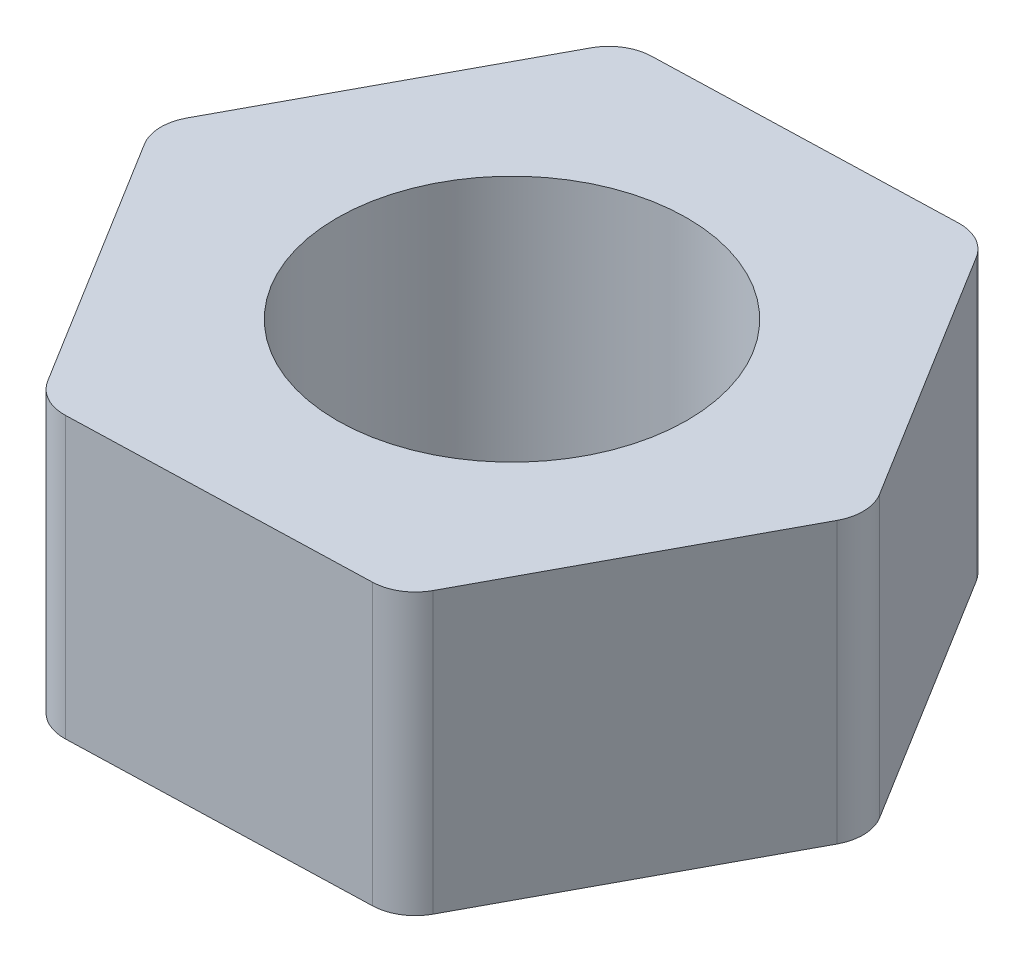
SolidWorks part; units mm, degrees
ref_plane "前视基准面" through (0, 0, 0) normal (0, 0, 1) x (1, 0, 0)
ref_plane "上视基准面" through (0, 0, 0) normal (0, 1, 0) x (1, 0, 0)
ref_plane "右视基准面" through (0, 0, 0) normal (1, 0, 0) x (0, 0, -1)
sketch "Sketch1" plane through (0, 0, 0) normal (0, 1, 0) x (1, 0, 0)
  line L1 (2.0955, -3.3881) -> (3.9819, 0.1207)
  line L2 (3.9819, 0.1207) -> (1.8864, 3.5088)
  line L3 (1.8864, 3.5088) -> (-2.0955, 3.3881)
  line L4 (-2.0955, 3.3881) -> (-3.9819, -0.1207)
  line L5 (-3.9819, -0.1207) -> (-1.8864, -3.5088)
  line L6 (-1.8864, -3.5088) -> (2.0955, -3.3881)
  circle A0 centre (0, 0) radius 2
  circle A1 centre (0, 0) radius 3.45 construction
  dimension "D1" = 6.9
  dimension "D2" = 4
extrude "Boss-Extrude1" add sketch "Sketch1" along normal blind 3.2
fillet "Fillet1" radius 0.5 6 edges at (-3.9819, 1.6, 0.1207) (-2.0955, 1.6, -3.3881) (1.8864, 1.6, -3.5088) (3.9819, 1.6, -0.1207) (2.0955, 1.6, 3.3881) (-1.8864, 1.6, 3.5088)
